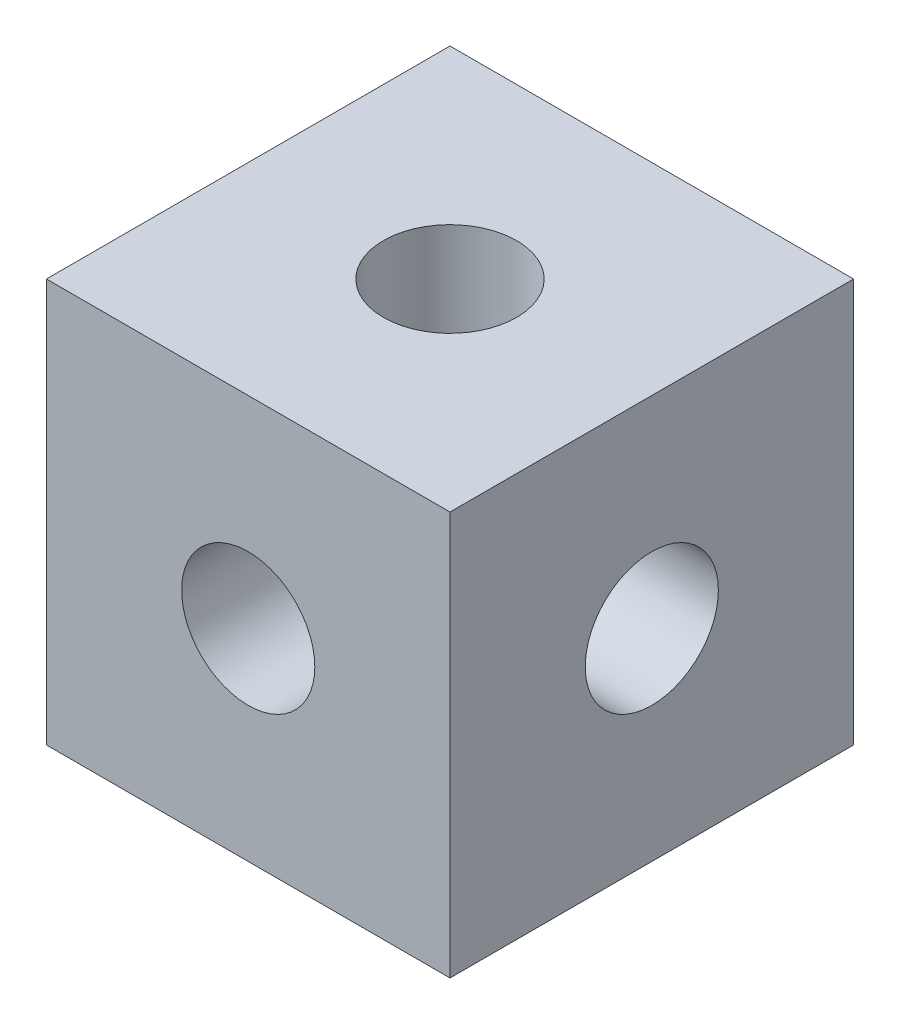
SolidWorks part; units mm, degrees
material "1060-H12 棒材(SS)"
ref_plane "前视基准面" through (0, 0, 0) normal (0, 0, 1) x (1, 0, 0)
ref_plane "上视基准面" through (0, 0, 0) normal (0, 1, 0) x (1, 0, 0)
ref_plane "右视基准面" through (0, 0, 0) normal (1, 0, 0) x (0, 0, -1)
sketch "草图1" plane through (0, 0, 0) normal (0, 1, 0) x (1, 0, 0)
  line L1 (-5, 5) -> (5, 5)
  line L2 (-5, 5) -> (-5, -5)
  line L3 (-5, -5) -> (5, -5)
  line L4 (5, 5) -> (5, -5)
  line L5 (-5, 5) -> (5, -5) construction
  line L6 (-5, -5) -> (5, 5) construction
  point P0 (0, 0)
  dimension "D1" = 10
  dimension "D2" = 10
extrude "凸台-拉伸1" add sketch "草图1" along normal blind 10
hole_wizard "孔1" positions "草图2" profile "草图3" legacy end condition up to next
sketch "草图2" plane through (0, 10, 0) normal (0, 1, 0) x (1, 0, 0)
  point P0 (0, 0)
sketch "草图3" plane through (0, 10, 0) normal (1, 0, 0) x (0, 0, 1)
  line L0 (0, 0) -> (0, 10)
  line L1 (0, 10) -> (1.65, 10)
  line L2 (1.65, 10) -> (1.65, 0)
  line L3 (1.65, 0) -> (0, 0)
  line L4 (0, 110) -> (0, -10) construction
  dimension "直径" = 3.3
  dimension "深度" = 10
sketch "草图6" plane through (5, 0, 0) normal (1, 0, 0) x (0, 0, -1)
  line L0 (-5, 0) -> (5, 10)
sketch "草图7" plane through (5, 0, 0) normal (1, 0, 0) x (0, 0, -1)
  line L0 (-5, 0) -> (5, 10) construction
  point P0 (0, 5)
hole_wizard "孔2" positions "草图7" profile "草图8" legacy end condition through all
sketch "草图8" plane through (5, 5, 0) normal (0, 1, 0) x (0, 0, -1)
  line L0 (0, 0) -> (0, 10)
  line L1 (0, 10) -> (1.65, 10)
  line L2 (1.65, 10) -> (1.65, 0)
  line L3 (1.65, 0) -> (0, 0)
  line L4 (0, 110) -> (0, -10) construction
  dimension "直径" = 3.3
  dimension "深度" = 10
sketch "草图9" plane through (0, 0, 5) normal (0, 0, 1) x (1, 0, 0)
  line L0 (-5, 0) -> (5, 10)
sketch "草图10" plane through (0, 0, 5) normal (0, 0, 1) x (1, 0, 0)
  line L0 (-5, 0) -> (5, 10) construction
  point P0 (0, 5)
hole_wizard "孔3" positions "草图10" profile "草图11" legacy end condition through all
sketch "草图11" plane through (0, 5, 5) normal (1, 0, 0) x (0, -1, 0)
  line L0 (0, 0) -> (0, 10)
  line L1 (0, 10) -> (1.65, 10)
  line L2 (1.65, 10) -> (1.65, 0)
  line L3 (1.65, 0) -> (0, 0)
  line L4 (0, 110) -> (0, -10) construction
  dimension "直径" = 3.3
  dimension "深度" = 10
